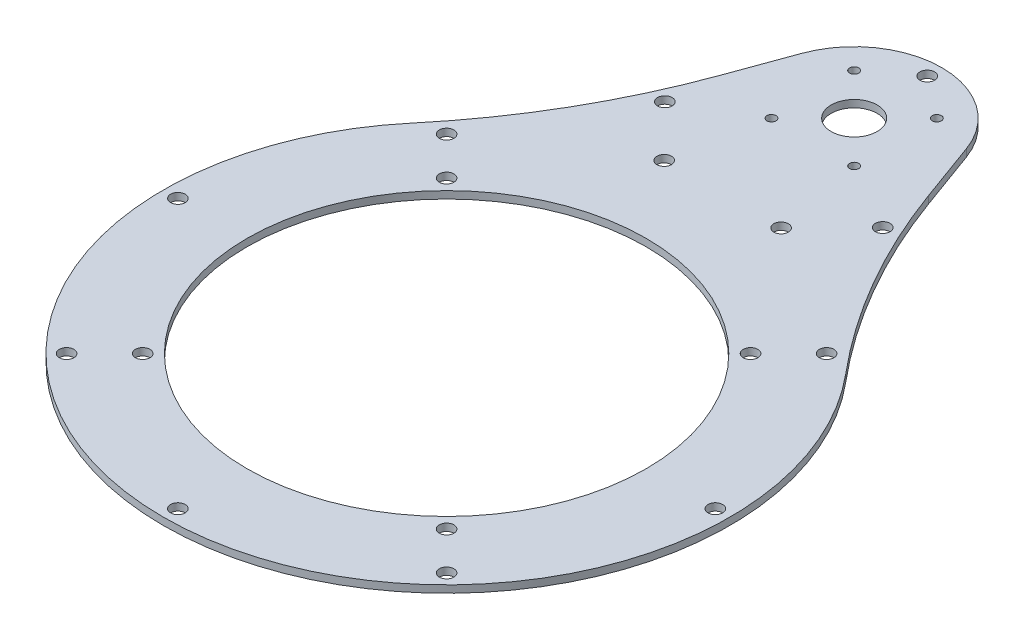
SolidWorks part; units mm, degrees
ref_plane "Front Plane" through (0, 0, 0) normal (0, 0, 1) x (1, 0, 0)
ref_plane "Top Plane" through (0, 0, 0) normal (0, 1, 0) x (1, 0, 0)
ref_plane "Right Plane" through (0, 0, 0) normal (1, 0, 0) x (0, 0, -1)
sketch "Sketch1" plane through (0, -64.8, 0) normal (0, -1, 0) x (1, 0, 0)
  line L0 (0, 0) -> (0, -177.075) construction
  line L1 (0, -177.075) -> (-17.9605, -159.1145) construction
  line L2 (0, -177.075) -> (10, -177.075) construction
  line L5 (-12.8024, -177.405) -> (-14.2912, -119.6387) construction
  line L6 (-62.7787, -39.3303) -> (-15.9829, -114.0253) construction
  line L7 (12.8024, -177.405) -> (14.2912, -119.6387) construction
  line L10 (62.7787, -39.3303) -> (15.9829, -114.0253) construction
  line L13 (0, 116.75) -> (0, 0) construction
  line L14 (35.8023, -190.106) -> (45.3132, -163.9748)
  line L15 (0, 0) -> (94.3001, -79.1272) construction
  line L16 (-35.8023, -190.106) -> (-45.3132, -163.9748)
  line L17 (0, 116.75) -> (0, 123.1) construction
  line L18 (0, -177.075) -> (0, -208.825) construction
  line L19 (0, -208.825) -> (0, -215.175) construction
  line L20 (-47.3293, -142.15) -> (-53.1206, -144.7545) construction
  circle A0 centre (0, 0) radius 86.7075 construction
  circle A1 centre (0, 0) radius 100.875
  circle A2 centre (0, 0) radius 100.875
  circle A3 centre (0, 0) radius 86.7075
  circle A4 centre (66.0261, 66.0261) radius 3.175 construction
  circle A5 centre (66.0261, 66.0261) radius 3.175
  circle A6 centre (66.0261, -66.0261) radius 3.175
  circle A7 centre (-66.0261, -66.0261) radius 3.175
  circle A8 centre (-66.0261, 66.0261) radius 3.175
  arc A16 (-35.8023, -190.106) -> (35.8023, -190.106) centre (0, -177.075) ccw
  arc A17 (45.3132, -163.9748) -> (94.3001, -79.1272) centre (310.4042, -260.46) cw
  arc A18 (-45.3132, -163.9748) -> (-94.3001, -79.1272) centre (-310.4042, -260.46) ccw
  arc A19 (94.3001, -79.1272) -> (-94.3001, -79.1272) centre (0, 0) ccw
  circle A20 centre (0, -177.075) radius 10
  circle A21 centre (-17.9605, -159.1145) radius 1.9844
  circle A22 centre (17.9605, -159.1145) radius 1.9844
  circle A23 centre (-17.9605, -195.0355) radius 1.9844
  circle A24 centre (17.9605, -195.0355) radius 1.9844
  arc A25 (-12.8024, -177.405) -> (12.8024, -177.405) centre (0, -177.075) ccw construction
  circle A26 centre (0, 0) radius 74.0813 construction
  arc A27 (62.7787, -39.3303) -> (-62.7787, -39.3303) centre (0, 0) ccw construction
  arc A28 (-14.2912, -119.6387) -> (-15.9829, -114.0253) centre (-25.4, -119.925) ccw construction
  circle A30 centre (-25.4, -119.925) radius 3.175
  arc A31 (14.2912, -119.6387) -> (15.9829, -114.0253) centre (25.4, -119.925) cw construction
  circle A33 centre (25.4, -119.925) radius 3.175
  circle A34 centre (0, -177.075) radius 12.8066 construction
  circle A35 centre (25.4, -119.925) radius 11.1125 construction
  circle A36 centre (25.4, -119.925) radius 11.1125 construction
  circle A37 centre (0, 116.75) radius 3.175
  circle A38 centre (82.5547, 82.5547) radius 3.175
  circle A39 centre (116.75, 0) radius 3.175
  circle A40 centre (82.5547, -82.5547) radius 3.175
  circle A41 centre (0, -116.75) radius 3.175 [skipped]
  circle A42 centre (-82.5547, -82.5547) radius 3.175
  circle A43 centre (-116.75, 0) radius 3.175
  circle A44 centre (-82.5547, 82.5547) radius 3.175
  circle A45 centre (0, -208.825) radius 3.175
  circle A46 centre (-47.3293, -142.15) radius 3.175
  circle A47 centre (47.3293, -142.15) radius 3.175
  point P18 (0, 0)
  point P32 (0, -100.875)
  point P76 (0, 0)
  dimension "D3" = 20
  dimension "D4" = 3.9688
  dimension "D8" = 38.1
  dimension "D10" = 20
  dimension "D9" = 22.225
  dimension "D12" = 6.35
  dimension "D13" = 6.35
  dimension "D14" = 6.35
  dimension "D5" = 25.4
  dimension "D6" = 45
  dimension "D7" = 76.2
  dimension "D11" = 50
  dimension "D15" = 25.4
  dimension "D16" = 19.05
  dimension "D18" = 73.025
  dimension "D1" = 0
  dimension "D2" = 4
  dimension "D17" = 8
extrude "Boss-Extrude1" add sketch "Sketch1" along normal blind 3.175
